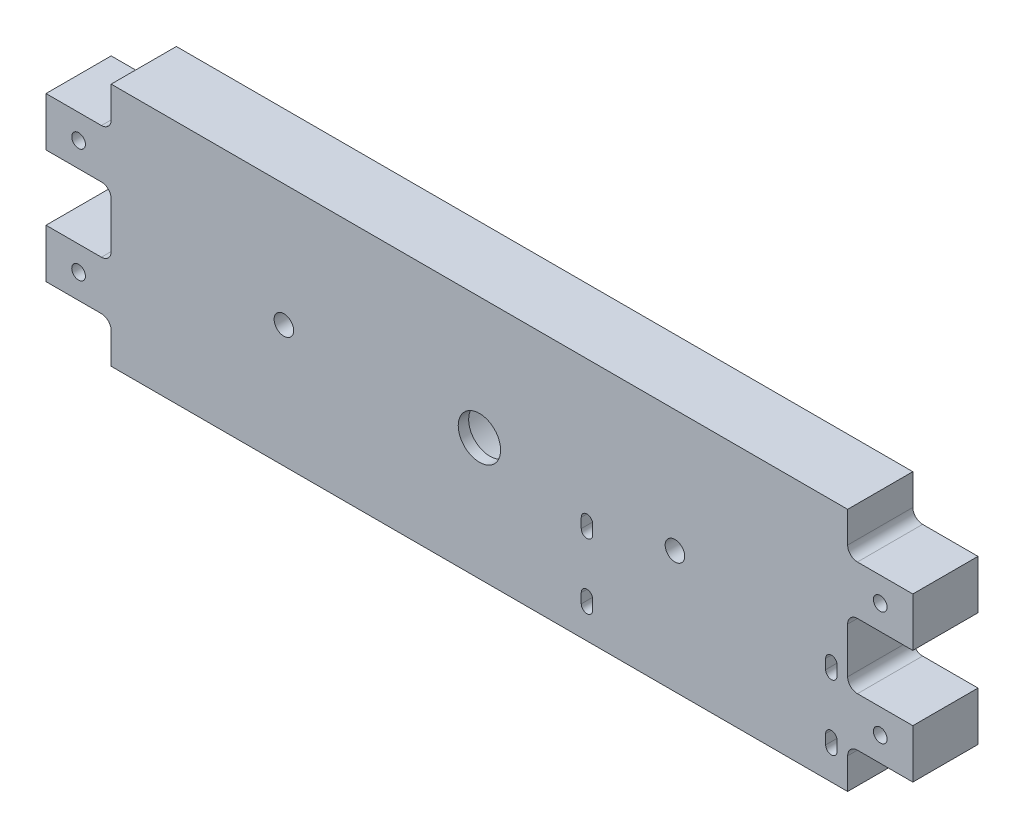
SolidWorks part; units mm, degrees
material "3.3547 (EN-AW 5083)"
ref_plane "Ebene vorne" through (0, 0, 0) normal (0, 0, 1) x (1, 0, 0)
ref_plane "Ebene oben" through (0, 0, 0) normal (0, 1, 0) x (1, 0, 0)
ref_plane "Ebene rechts" through (0, 0, 0) normal (1, 0, 0) x (0, 0, -1)
sketch "Skizze1" plane through (0, 0, 0) normal (0, 0, 1) x (1, 0, 0)
  line L1 (-89.4763, 33.2443) -> (176.5237, 33.2443)
  line L2 (-89.4763, 33.2443) -> (-89.4763, -46.7557)
  line L3 (-89.4763, -46.7557) -> (176.5237, -46.7557)
  line L4 (176.5237, 33.2443) -> (176.5237, -46.7557)
  dimension "D1" = 266
  dimension "D2" = 80
extrude "Aufsatz-Linear austragen1" add sketch "Skizze1" along normal blind 20
sketch "Skizze4" plane through (0, 0, 0) normal (0, 0, -1) x (-1, 0, 0)
  line L0 (-43.5237, 33.2443) -> (-43.5237, -46.7557) construction
  line L1 (-176.5237, 33.2443) -> (89.4763, 33.2443) construction
  line L2 (89.4763, -46.7557) -> (-176.5237, -46.7557) construction
  circle A0 centre (-43.5237, -6.7557) radius 6.5
extrude "Schnitt-Linear austragen1" cut sketch "Skizze4" against normal blind 20
sketch "Skizze9" plane through (0, 0, 0) normal (0, 0, -1) x (-1, 0, 0)
  circle A0 centre (-43.5237, -6.7557) radius 15
extrude "Schnitt-Linear austragen5" cut sketch "Skizze9" against normal blind 16.8
sketch "Skizze10" plane through (0, 0, 20) normal (0, 0, 1) x (1, 0, 0)
  line L1 (-89.4763, 33.2443) -> (-69.4763, 33.2443)
  line L2 (-89.4763, 33.2443) -> (-89.4763, 18.2443)
  line L3 (-89.4763, 18.2443) -> (-69.4763, 18.2443)
  line L4 (-69.4763, 33.2443) -> (-69.4763, 18.2443)
  line L5 (-89.4763, -46.7557) -> (-69.4763, -46.7557)
  line L6 (-89.4763, -46.7557) -> (-89.4763, -31.7557)
  line L7 (-89.4763, -31.7557) -> (-69.4763, -31.7557)
  line L8 (-69.4763, -46.7557) -> (-69.4763, -31.7557)
  line L9 (176.5237, -46.7557) -> (156.5237, -46.7557)
  line L10 (176.5237, -46.7557) -> (176.5237, -31.7557)
  line L11 (176.5237, -31.7557) -> (156.5237, -31.7557)
  line L12 (156.5237, -46.7557) -> (156.5237, -31.7557)
  line L13 (176.5237, 33.2443) -> (156.5237, 33.2443)
  line L14 (176.5237, 33.2443) -> (176.5237, 18.2443)
  line L15 (176.5237, 18.2443) -> (156.5237, 18.2443)
  line L16 (156.5237, 33.2443) -> (156.5237, 18.2443)
  dimension "D1" = 20
  dimension "D2" = 15
  dimension "D3" = 15
  dimension "D4" = 20
extrude "Schnitt-Linear austragen6" cut sketch "Skizze10" against normal blind 24.3
sketch "Skizze11" plane through (-89.4763, 0, 0) normal (-1, 0, 0) x (0, 0, 1)
  line L3 (25.2623, -44.2557) -> (-4.958, -44.2557)
  line L4 (25.2623, -44.2557) -> (25.2623, 30.7443)
  line L5 (25.2623, 30.7443) -> (-4.958, 30.7443)
  line L6 (-4.958, -44.2557) -> (-4.958, 30.7443)
  line L7 (10.1521, 30.7443) -> (10.1521, -44.2557) construction
  line L8 (25.2623, -6.7557) -> (-4.958, -6.7557) construction
  line L9 (55.8439, -60.0809) -> (-35.5396, -60.0809)
  line L10 (55.8439, -60.0809) -> (55.8439, 46.5696)
  line L11 (55.8439, 46.5696) -> (-35.5396, 46.5696)
  line L12 (-35.5396, -60.0809) -> (-35.5396, 46.5696)
  line L13 (10.1521, 46.5696) -> (10.1521, -60.0809) construction
  line L14 (55.8439, -6.7557) -> (-35.5396, -6.7557) construction
  dimension "D1" = 75
extrude "Schnitt-Linear austragen7" cut sketch "Skizze11" against normal blind 304.3
sketch "Skizze12" plane through (0, 0, 0) normal (0, 0, -1) x (-1, 0, 0)
  circle A0 centre (-43.5237, -6.7557) radius 24.75
extrude "Schnitt-Linear austragen8" cut sketch "Skizze12" against normal blind 3
sketch "Skizze13" plane through (-89.4763, 0, 0) normal (-1, 0, 0) x (0, 0, 1)
  line L0 (0, 18.2443) -> (0, -31.7557) construction
  line L1 (0, 3.2443) -> (20, 3.2443)
  line L2 (0, 3.2443) -> (0, -16.7557)
  line L3 (0, -16.7557) -> (20, -16.7557)
  line L4 (20, 3.2443) -> (20, -16.7557)
  line L5 (20, 18.2443) -> (20, -31.7557) construction
  line L6 (0, 18.2443) -> (20, 18.2443) construction
  dimension "D1" = 15
  dimension "D2" = 20
extrude "Schnitt-Linear austragen10" cut sketch "Skizze13" against normal blind 20
fillet "Verrundung1" radius 3 4 edges at (-69.4763, -31.7557, 10) (-69.4763, -16.7557, 10) (-69.4763, 18.2443, 10) (-69.4763, 3.2443, 10)
sketch "Skizze14" plane through (176.5237, 0, 0) normal (1, 0, 0) x (0, 0, -1)
  line L1 (-20, 3.2443) -> (0, 3.2443)
  line L2 (-20, 3.2443) -> (-20, -16.7557)
  line L3 (-20, -16.7557) -> (0, -16.7557)
  line L4 (0, 3.2443) -> (0, -16.7557)
extrude "Schnitt-Linear austragen11" cut sketch "Skizze14" against normal blind 20
fillet "Verrundung2" radius 3 4 edges at (156.5237, -31.7557, 10) (156.5237, 3.2443, 10) (156.5237, -16.7557, 10) (156.5237, 18.2443, 10)
sketch "Skizze15" plane through (0, 0, 0) normal (0, 0, -1) x (-1, 0, 0)
  circle A0 centre (79.4763, 10.7443) radius 2
  circle A1 centre (79.4763, -24.2557) radius 2
  circle A2 centre (-166.5237, 10.7443) radius 2
  circle A3 centre (-166.5237, -24.2557) radius 2
extrude "Schnitt-Linear austragen12" cut sketch "Skizze15" against normal blind 20
hole_wizard "M5 Gewindebohrung1" positions "3D-Skizze1" profile "Skizze16" tap size "M5" standard "DIN" end condition through all
sketch3d "3D-Skizze1"
  line L0 (166.5237, 10.7443, 20) -> (166.5237, 10.7443, 0) construction
  line L1 (166.5237, -24.2557, 20) -> (166.5237, -24.2557, 0) construction
  line L2 (-79.4763, 10.7443, 20) -> (-79.4763, 10.7443, 0) construction
  line L3 (-79.4763, -24.2557, 20) -> (-79.4763, -24.2557, 0) construction
  point P0 (166.5237, 10.7443, 0)
  point P4 (166.5237, -24.2557, 0)
  point P8 (-79.4763, 10.7443, 0)
  point P12 (-79.4763, -24.2557, 0)
sketch "Skizze16" plane through (166.5237, 10.7443, 0) normal (1, 0, 0) x (0, 1, 0)
  line L0 (0, 0) -> (0, 20)
  line L1 (0, 20) -> (2.1, 20)
  line L2 (2.1, 20) -> (2.1, 0.425)
  line L3 (2.1, 0.425) -> (2.525, 0)
  line L5 (2.525, 0) -> (0, 0)
  line L6 (-2.1, 0.425) -> (-2.525, 0) construction
  line L11 (0, -6.35) -> (0, 107.95) construction
  dimension "Bohrerdurchmesser" = 4.2
  dimension "Bohrungstiefe" = 20
  dimension "Senkdurchmesser (Oben)" = 5.05
  dimension "Senkwinkel (Oben)" = 90
cosmetic thread "Bohrungsgewinde3" parameters "D2"=5
cosmetic thread "Bohrungsgewinde4" parameters "D2"=5
cosmetic thread "Bohrungsgewinde5" parameters "D2"=5
cosmetic thread "Bohrungsgewinde6" parameters "D2"=5
sketch "Skizze17" plane through (0, 0, 0) normal (0, 0, -1) x (-1, 0, 0)
  line L4 (-151.5237, -13.7557) -> (-76.5237, -13.7557) construction
  line L5 (-76.5237, -13.7557) -> (-76.5237, -33.7557) construction
  line L6 (-76.5237, -33.7557) -> (-151.5237, -33.7557) construction
  line L7 (-151.5237, -33.7557) -> (-151.5237, -13.7557) construction
  line L8 (-176.5237, -31.7557) -> (-159.5237, -31.7557) construction
  line L10 (-176.5237, -31.7557) -> (-176.5237, -16.7557) construction
  line L11 (-151.5237, -12.2557) -> (-151.5237, -15.2557) construction
  line L12 (-149.7737, -12.2557) -> (-149.7737, -15.2557)
  line L13 (-153.2737, -12.2557) -> (-153.2737, -15.2557)
  line L14 (-76.5237, -12.2557) -> (-76.5237, -15.2557) construction
  line L15 (-74.7737, -12.2557) -> (-74.7737, -15.2557)
  line L16 (-78.2737, -12.2557) -> (-78.2737, -15.2557)
  line L17 (-76.5237, -32.2557) -> (-76.5237, -35.2557) construction
  line L18 (-74.7737, -32.2557) -> (-74.7737, -35.2557)
  line L19 (-78.2737, -32.2557) -> (-78.2737, -35.2557)
  line L20 (-151.5237, -32.2557) -> (-151.5237, -35.2557) construction
  line L21 (-149.7737, -32.2557) -> (-149.7737, -35.2557)
  line L22 (-153.2737, -32.2557) -> (-153.2737, -35.2557)
  arc A9 (-149.7737, -12.2557) -> (-153.2737, -12.2557) centre (-151.5237, -12.2557) ccw
  arc A10 (-153.2737, -15.2557) -> (-149.7737, -15.2557) centre (-151.5237, -15.2557) ccw
  arc A11 (-74.7737, -12.2557) -> (-78.2737, -12.2557) centre (-76.5237, -12.2557) ccw
  arc A12 (-78.2737, -15.2557) -> (-74.7737, -15.2557) centre (-76.5237, -15.2557) ccw
  arc A13 (-74.7737, -32.2557) -> (-78.2737, -32.2557) centre (-76.5237, -32.2557) ccw
  arc A14 (-78.2737, -35.2557) -> (-74.7737, -35.2557) centre (-76.5237, -35.2557) ccw
  arc A15 (-149.7737, -32.2557) -> (-153.2737, -32.2557) centre (-151.5237, -32.2557) ccw
  arc A16 (-153.2737, -35.2557) -> (-149.7737, -35.2557) centre (-151.5237, -35.2557) ccw
  point P11 (-151.5237, -13.7557)
  point P18 (-76.5237, -13.7557)
  point P25 (-76.5237, -33.7557)
  point P32 (-151.5237, -33.7557)
  dimension "D1" = 18
  dimension "D2" = 25
  dimension "D3" = 75
  dimension "D4" = 20
extrude "Schnitt-Linear austragen13" cut sketch "Skizze17" against normal blind 30
sketch "Skizze18" plane through (0, 0, 0) normal (0, 0, -1) x (-1, 0, 0)
  line L0 (-151.5237, -9.7189) -> (-151.5237, -18.7189) construction
  line L1 (-148.5237, -9.7189) -> (-148.5237, -18.7189)
  line L2 (-154.5237, -9.7189) -> (-154.5237, -18.7189)
  line L3 (-151.5237, -29.2557) -> (-151.5237, -38.2557) construction
  line L4 (-148.5237, -29.2557) -> (-148.5237, -38.2557)
  line L5 (-154.5237, -29.2557) -> (-154.5237, -38.2557)
  line L6 (-76.5237, -9.2557) -> (-76.5237, -18.2557) construction
  line L7 (-73.5237, -9.2557) -> (-73.5237, -18.2557)
  line L8 (-79.5237, -9.2557) -> (-79.5237, -18.2557)
  line L9 (-76.5237, -29.2557) -> (-76.5237, -38.2557) construction
  line L10 (-73.5237, -29.2557) -> (-73.5237, -38.2557)
  line L11 (-79.5237, -29.2557) -> (-79.5237, -38.2557)
  arc A0 (-148.5237, -9.7189) -> (-154.5237, -9.7189) centre (-151.5237, -9.7189) ccw
  arc A1 (-154.5237, -18.7189) -> (-148.5237, -18.7189) centre (-151.5237, -18.7189) ccw
  arc A2 (-148.5237, -29.2557) -> (-154.5237, -29.2557) centre (-151.5237, -29.2557) ccw
  arc A3 (-154.5237, -38.2557) -> (-148.5237, -38.2557) centre (-151.5237, -38.2557) ccw
  arc A4 (-73.5237, -9.2557) -> (-79.5237, -9.2557) centre (-76.5237, -9.2557) ccw
  arc A5 (-79.5237, -18.2557) -> (-73.5237, -18.2557) centre (-76.5237, -18.2557) ccw
  arc A6 (-73.5237, -29.2557) -> (-79.5237, -29.2557) centre (-76.5237, -29.2557) ccw
  arc A7 (-79.5237, -38.2557) -> (-73.5237, -38.2557) centre (-76.5237, -38.2557) ccw
  point P2 (-151.5237, -14.2189)
  point P11 (-151.5237, -33.7557)
  point P18 (-76.5237, -13.7557)
  point P25 (-76.5237, -33.7557)
extrude "Schnitt-Linear austragen14" cut sketch "Skizze18" against normal blind 6
sketch "Skizze19" plane through (0, 0, 0) normal (0, 0, -1) x (-1, 0, 0)
  circle A0 centre (16.4763, -6.7557) radius 3
  circle A1 centre (-103.5237, -6.7557) radius 3
  circle A2 centre (-43.5237, -6.7557) radius 6.5 construction
  dimension "D1" = 60
  dimension "D2" = 60
extrude "Schnitt-Linear austragen15" cut sketch "Skizze19" against normal blind 20
sketch "Skizze20" plane through (0, 0, 0) normal (0, 0, -1) x (-1, 0, 0)
  circle A0 centre (-151.5237, -13.7557) radius 2
  circle A1 centre (-151.5237, -33.7557) radius 2
  circle A2 centre (-76.5237, -33.7557) radius 2
  circle A3 centre (-76.5237, -13.7557) radius 2
